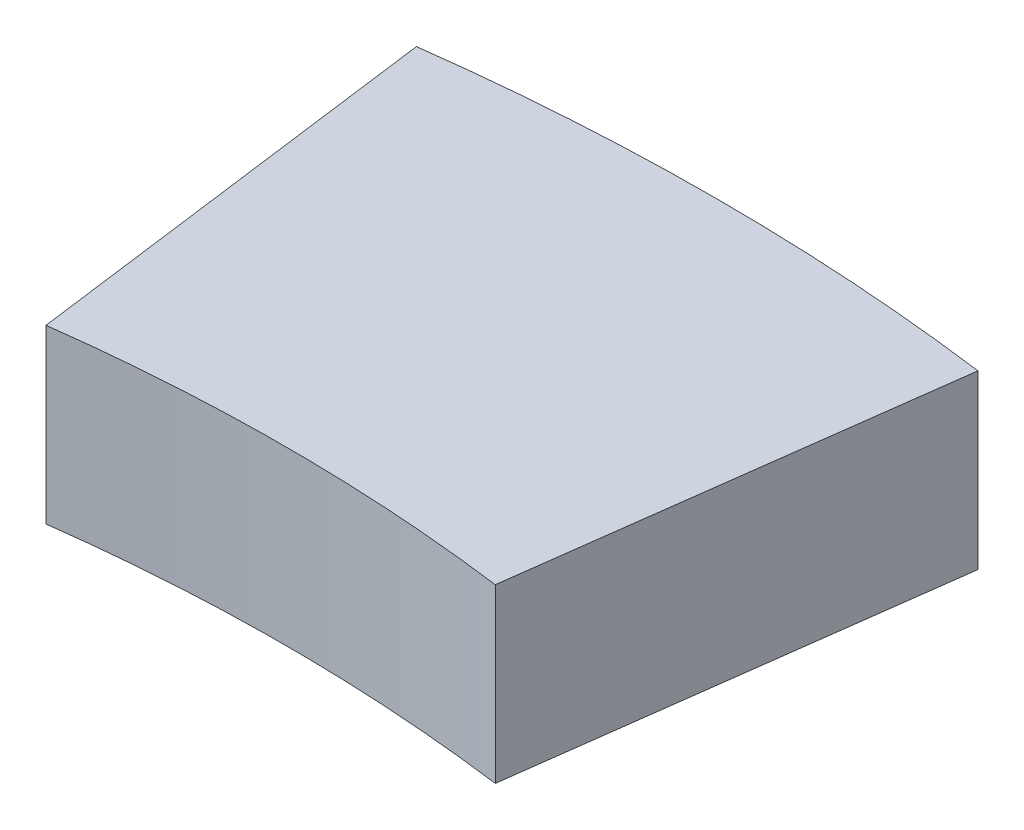
SolidWorks part; units mm, degrees
ref_plane "Front Plane" through (0, 0, 0) normal (0, 0, 1) x (1, 0, 0)
ref_plane "Top Plane" through (0, 0, 0) normal (0, 1, 0) x (1, 0, 0)
ref_plane "Right Plane" through (0, 0, 0) normal (1, 0, 0) x (0, 0, -1)
sketch "Sketch1" plane through (0, 0, 0) normal (0, 1, 0) x (1, 0, 0)
  line L0 (0, 250) -> (0, 0) construction
  line L1 (32.6315, 247.8612) -> (26.1052, 198.289)
  line L2 (-32.6315, 247.8612) -> (-26.1052, 198.289)
  arc A0 (32.6315, 247.8612) -> (-32.6315, 247.8612) centre (0, 0) ccw
  arc A1 (26.1052, 198.289) -> (-26.1052, 198.289) centre (0, 0) ccw
  arc A2 (-26.1052, 198.289) -> (26.1052, 198.289) centre (0, 0) ccw construction
  arc A3 (-32.6315, 247.8612) -> (32.6315, 247.8612) centre (0, 0) ccw construction
  dimension "D1" = 500
  dimension "D2" = 400
  dimension "D5" = 200
  dimension "D3" = 7.5
  dimension "D4" = 15
  dimension "D6" = 50
extrude "Boss-Extrude1" add sketch "Sketch1" along normal mid plane 20
